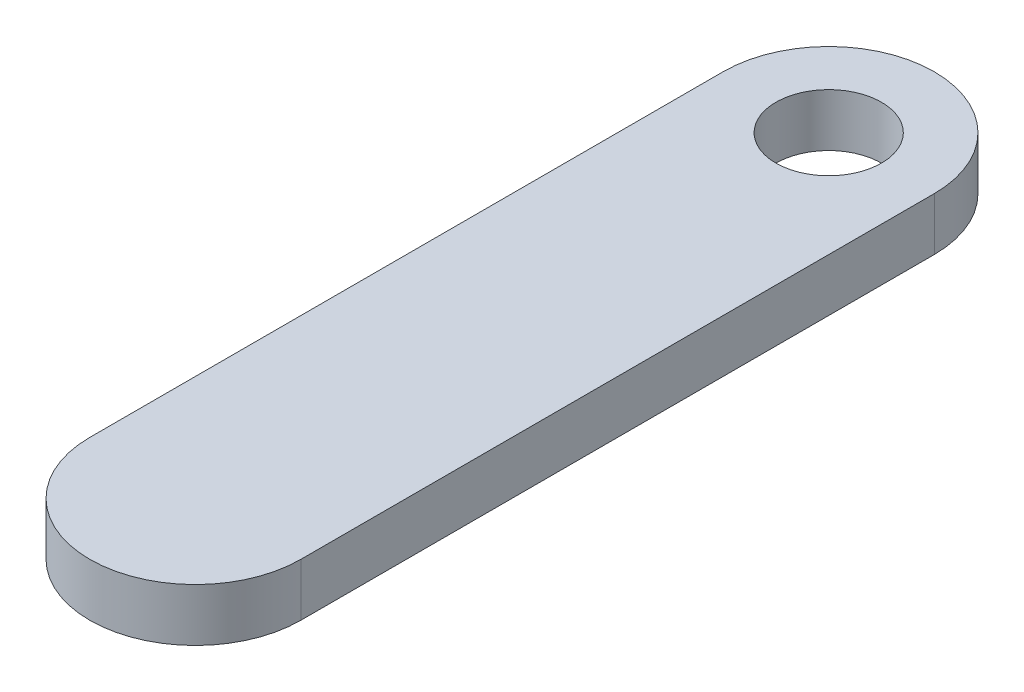
SolidWorks part; units mm, degrees
ref_plane "Front Plane" through (0, 0, 0) normal (0, 0, 1) x (1, 0, 0)
ref_plane "Top Plane" through (0, 0, 0) normal (0, 1, 0) x (1, 0, 0)
ref_plane "Right Plane" through (0, 0, 0) normal (1, 0, 0) x (0, 0, -1)
sketch "Sketch1" plane through (0, 0, 0) normal (0, 1, 0) x (1, 0, 0)
  line L0 (0, 0) -> (0, -76.2) construction
  line L1 (12.7, 0) -> (12.7, -76.2)
  line L2 (-12.7, 0) -> (-12.7, -76.2)
  arc A0 (12.7, 0) -> (-12.7, 0) centre (0, 0) ccw
  arc A1 (-12.7, -76.2) -> (12.7, -76.2) centre (0, -76.2) ccw
  circle A2 centre (0, 0) radius 6.35
  point P3 (0, -38.1)
  dimension "D2" = 12.7
  dimension "D3" = 12.7
  dimension "D1" = 76.2
extrude "Boss-Extrude1" add sketch "Sketch1" along normal blind 6.35
